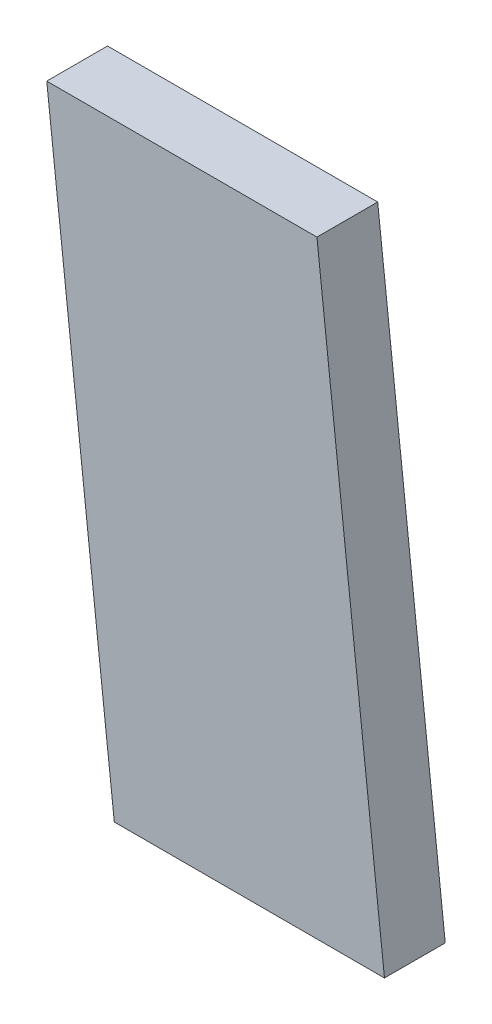
SolidWorks part; units mm, degrees
ref_plane "Front Plane" through (0, 0, 0) normal (0, 0, 1) x (1, 0, 0)
ref_plane "Top Plane" through (0, 0, 0) normal (0, 1, 0) x (1, 0, 0)
ref_plane "Right Plane" through (0, 0, 0) normal (1, 0, 0) x (0, 0, -1)
sketch "Sketch1" plane through (0, 0, 0) normal (0, 0, 1) x (1, 0, 0)
  line L0 (1300, 500) -> (1280, 680)
  line L1 (1280, 680) -> (1360, 680)
  line L2 (1360, 680) -> (1380, 500)
  line L3 (1380, 500) -> (1300, 500)
extrude "Boss-Extrude1" add sketch "Sketch1" along normal blind 18
